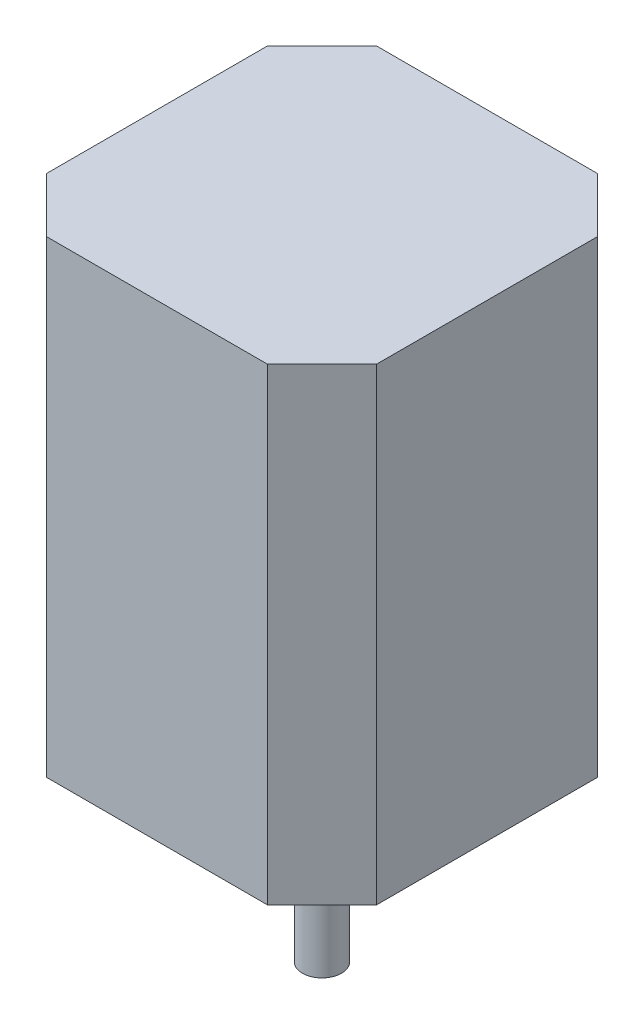
SolidWorks part; units mm, degrees
ref_plane "前视基准面" through (0, 0, 0) normal (0, 0, 1) x (1, 0, 0)
ref_plane "上视基准面" through (0, 0, 0) normal (0, 1, 0) x (1, 0, 0)
ref_plane "右视基准面" through (0, 0, 0) normal (1, 0, 0) x (0, 0, -1)
sketch "草图1" plane through (0, 0, 0) normal (0, 1, 0) x (1, 0, 0)
  line L0 (14.15, -21.15) -> (21.15, -14.15)
  line L1 (-14.15, -21.15) -> (14.15, -21.15)
  line L2 (-21.15, -14.15) -> (-21.15, 14.15)
  line L3 (-14.15, 21.15) -> (14.15, 21.15)
  line L4 (21.15, -14.15) -> (21.15, 14.15)
  line L5 (-21.15, -21.15) -> (21.15, 21.15) construction
  line L6 (-21.15, 21.15) -> (21.15, -21.15) construction
  line L7 (-21.15, -14.15) -> (-14.15, -21.15)
  line L8 (-21.15, 14.15) -> (-14.15, 21.15)
  line L9 (14.15, 21.15) -> (21.15, 14.15)
  point P0 (0, 0)
  point P19 (0, 0)
  point P22 (0, 0)
  point P25 (0, 0)
  point P28 (0, 0)
  dimension "D1" = 42.3
  dimension "D2" = 42.3
  dimension "D5" = 4
extrude "凸台-拉伸1" add sketch "草图1" along normal blind 60
sketch "草图2" plane through (0, 0, 0) normal (0, -1, 0) x (1, 0, 0)
  circle A0 centre (0, 0) radius 11
  dimension "D1" = 22
extrude "凸台-拉伸2" add sketch "草图2" along normal blind 2
sketch "草图3" plane through (0, -2, 0) normal (0, -1, 0) x (1, 0, 0)
  circle A0 centre (0, 0) radius 2.5
  dimension "D1" = 5
sketch "草图4" plane through (0, 0, 0) normal (0, -1, 0) x (1, 0, 0)
  line L0 (-14.15, 21.15) -> (14.15, 21.15) construction
  line L1 (21.15, 14.15) -> (21.15, -14.15) construction
  line L2 (-21.15, -14.15) -> (-21.15, 14.15) construction
  circle A0 centre (15.5, 15.5) radius 1.5
  circle A1 centre (15.5, -15.5) radius 1.5
  circle A2 centre (-15.5, -15.5) radius 1.5
  circle A3 centre (-15.5, 15.5) radius 1.5
  point P15 (0, 0)
  dimension "D1" = 3
  dimension "D2" = 5.65
  dimension "D3" = 5.65
  dimension "D6" = 31
  dimension "D7" = 31
  dimension "D5" = 5.65
  dimension "D4" = 4
extrude "切除-拉伸1" cut sketch "草图4" against normal blind 4.5
extrude "凸台-拉伸3" add sketch "草图3" along normal blind 22 contours A0
